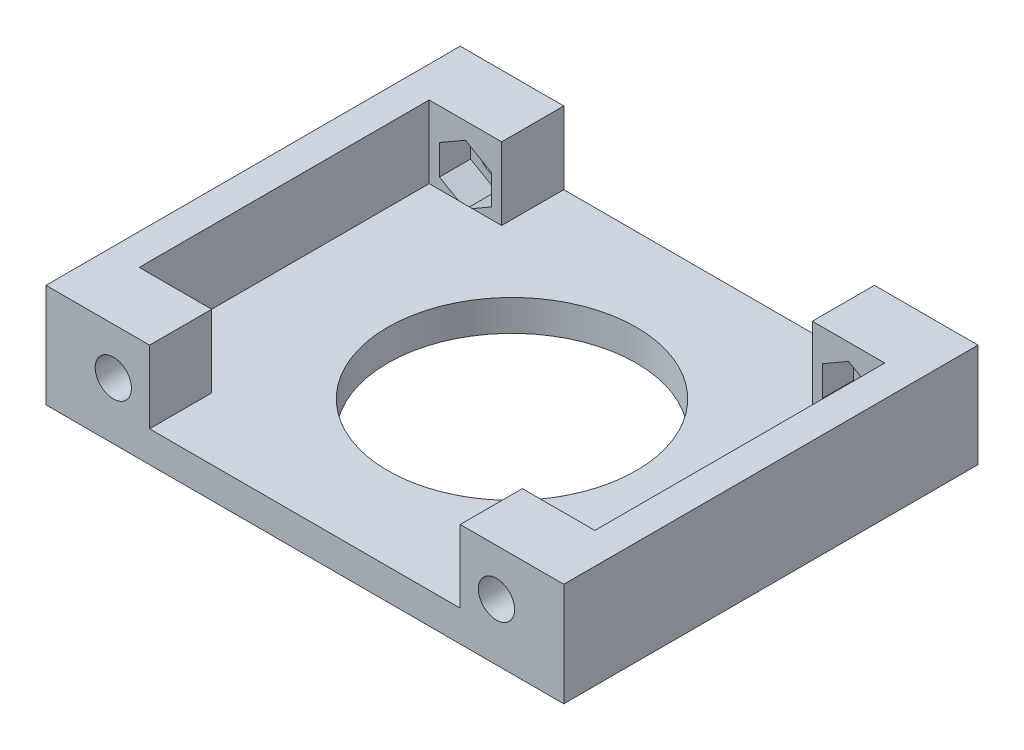
SolidWorks part; units mm, degrees
ref_plane "Front Plane" through (0, 0, 0) normal (0, 0, 1) x (1, 0, 0)
ref_plane "Top Plane" through (0, 0, 0) normal (0, 1, 0) x (1, 0, 0)
ref_plane "Right Plane" through (0, 0, 0) normal (1, 0, 0) x (0, 0, -1)
sketch "Sketch1" plane through (0, 0, 0) normal (0, 1, 0) x (1, 0, 0)
  line L1 (-25, 20) -> (25, 20)
  line L2 (-25, 20) -> (-25, -20)
  line L3 (-25, -20) -> (25, -20)
  line L4 (25, 20) -> (25, -20)
  line L5 (-25, 20) -> (25, -20) construction
  line L6 (-25, -20) -> (25, 20) construction
  point P0 (0, 0)
  dimension "D1" = 50
  dimension "D2" = 40
extrude "Boss-Extrude1" add sketch "Sketch1" along normal blind 3
sketch "Sketch2" plane through (0, 3, 0) normal (0, 1, 0) x (1, 0, 0)
  circle A0 centre (0, 0) radius 12
  dimension "D1" = 24
extrude "Cut-Extrude1" cut sketch "Sketch2" against normal through all
sketch "Sketch3" plane through (0, 3, 0) normal (0, 1, 0) x (1, 0, 0)
  line L0 (-25, -20) -> (25, -20) construction
  line L1 (-25, 20) -> (-22, 20)
  line L2 (-25, 20) -> (-25, -20)
  line L3 (-25, -20) -> (-22, -20)
  line L4 (-22, 20) -> (-22, -20)
  line L6 (22, -20) -> (25, -20)
  line L7 (22, -20) -> (22, 20)
  line L8 (22, 20) -> (25, 20)
  line L9 (25, -20) -> (25, 20)
  dimension "D1" = 3
extrude "Boss-Extrude2" add sketch "Sketch3" along normal blind 7
sketch "Sketch4" plane through (0, 0, 20) normal (0, 0, 1) x (1, 0, 0)
  line L1 (-22, 3) -> (-15, 3)
  line L2 (-22, 3) -> (-22, 10)
  line L3 (-22, 10) -> (-15, 10)
  line L4 (-15, 3) -> (-15, 10)
  line L5 (22, 3) -> (15, 3)
  line L6 (22, 3) -> (22, 10)
  line L7 (22, 10) -> (15, 10)
  line L8 (15, 3) -> (15, 10)
  dimension "D2" = 7
  dimension "6" = 7
extrude "Boss-Extrude3" add sketch "Sketch4" against normal blind 6
sketch "Sketch5" plane through (0, 0, 20) normal (0, 0, 1) x (1, 0, 0)
  line L0 (-18.5, 10) -> (-18.5, 5.5) construction
  line L2 (18.5, 10) -> (18.5, 5.5) construction
  line L3 (-25, 0) -> (25, 0) construction
  line L4 (-18.5, 5.5) -> (18.5, 5.5) construction
  line L6 (-22, 10) -> (-15, 10) construction
  line L7 (-25, 10) -> (-15, 10) construction
  line L8 (15, 10) -> (22, 10) construction
  line L9 (15, 10) -> (15, 3) construction
  line L10 (15, 10) -> (25, 10) construction
  circle A0 centre (-18.5, 5.5) radius 1.75
  circle A1 centre (18.5, 5.5) radius 1.75
  dimension "D1" = 3.5
  dimension "D2" = 3.5
  dimension "D3" = 5.5
extrude "Cut-Extrude2" cut sketch "Sketch5" against normal through all
mirror "Mirror1" about plane through (0, 0, 0) normal (0, 0, 1) of "Cut-Extrude2", "Boss-Extrude3"
sketch "Sketch6" plane through (0, 0, -14) normal (0, 0, 1) x (1, 0, 0)
  line L1 (-18.5, 2.6132) -> (-16, 4.0566)
  line L2 (-16, 4.0566) -> (-16, 6.9434)
  line L3 (-16, 6.9434) -> (-18.5, 8.3868)
  line L4 (-18.5, 8.3868) -> (-21, 6.9434)
  line L5 (-21, 6.9434) -> (-21, 4.0566)
  line L6 (-21, 4.0566) -> (-18.5, 2.6132)
  circle A0 centre (-18.5, 5.5) radius 2.5 construction
  dimension "D1" = 5
extrude "Cut-Extrude3" cut sketch "Sketch6" against normal blind 3
mirror "Mirror2" about plane through (0, 0, 0) normal (1, 0, 0) of "Cut-Extrude3"
mirror "Mirror3" about plane through (0, 0, 0) normal (0, 0, 1) of "Mirror2", "Cut-Extrude3"
